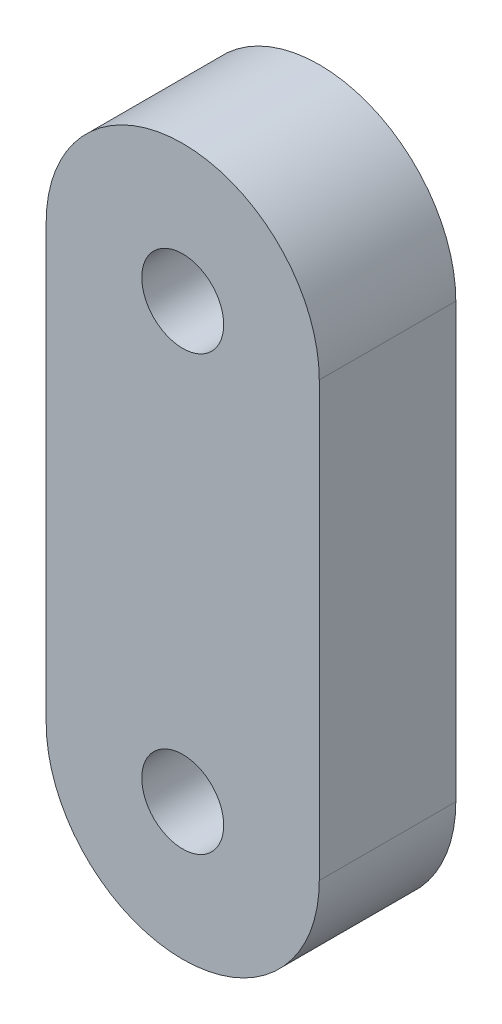
SolidWorks part; units mm, degrees
material "Thornel Mat VMA"
ref_plane "前视基准面" through (0, 0, 0) normal (0, 0, 1) x (1, 0, 0)
ref_plane "上视基准面" through (0, 0, 0) normal (0, 1, 0) x (1, 0, 0)
ref_plane "右视基准面" through (0, 0, 0) normal (1, 0, 0) x (0, 0, -1)
sketch "草图1" plane through (0, 0, 0) normal (0, 0, 1) x (1, 0, 0)
  line L0 (0, -6.35) -> (0, 6.35) construction
  line L1 (-4, -6.35) -> (-4, 6.35)
  line L2 (4, -6.35) -> (4, 6.35)
  arc A0 (-4, -6.35) -> (4, -6.35) centre (0, -6.35) ccw
  arc A1 (4, 6.35) -> (-4, 6.35) centre (0, 6.35) ccw
  circle A2 centre (0, 6.35) radius 1.2
  circle A3 centre (0, -6.35) radius 1.2
  point P2 (0, 0)
  dimension "D2" = 2.4
  dimension "D3" = 4
  dimension "D1" = 12.7
extrude "凸台-拉伸1" add sketch "草图1" along normal blind 4
